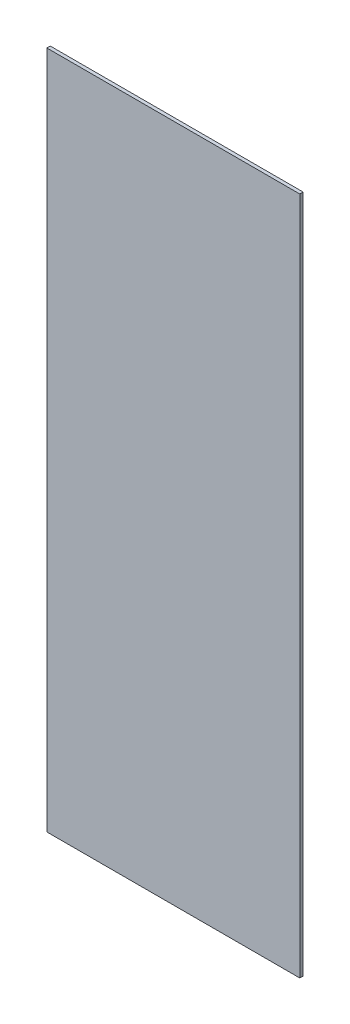
SolidWorks part; units mm, degrees
ref_plane "Front Plane" through (0, 0, 0) normal (0, 0, 1) x (1, 0, 0)
ref_plane "Top Plane" through (0, 0, 0) normal (0, 1, 0) x (1, 0, 0)
ref_plane "Right Plane" through (0, 0, 0) normal (1, 0, 0) x (0, 0, -1)
sketch "Sketch2" plane through (0, 0, 0) normal (0, 0, 1) x (1, 0, 0)
  line L1 (-74.5, 200) -> (74.5, 200)
  line L2 (-74.5, 200) -> (-74.5, -200)
  line L3 (-74.5, -200) -> (74.5, -200)
  line L4 (74.5, 200) -> (74.5, -200)
  line L5 (-74.5, 200) -> (74.5, -200) construction
  line L6 (-74.5, -200) -> (74.5, 200) construction
  point P0 (0, 0)
  dimension "D1" = 400
  dimension "D2" = 149
extrude "Boss-Extrude1" add sketch "Sketch2" along normal blind 2
